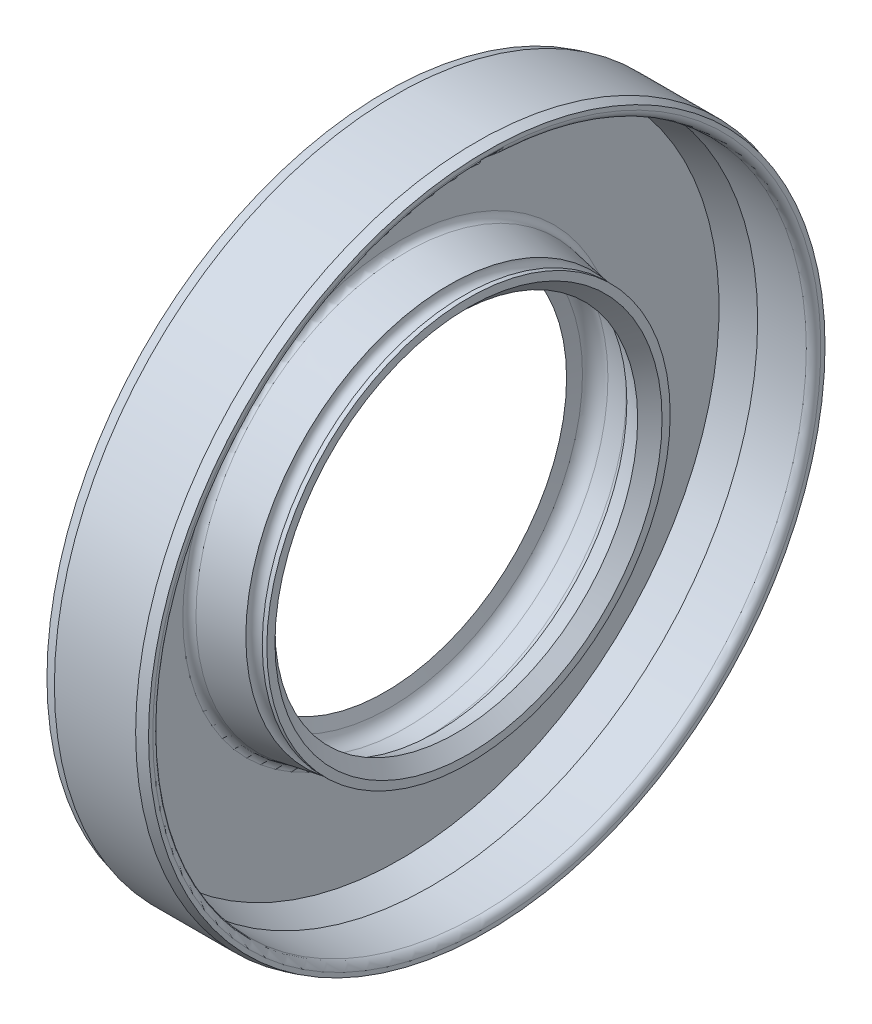
SolidWorks part; units mm, degrees
material "NBR"
ref_plane "Horní rovina" through (0, 0, 0) normal (0, 0, 1) x (1, 0, 0)
ref_plane "Přední rovina" through (0, 0, 0) normal (0, 1, 0) x (1, 0, 0)
ref_plane "Pravá rovina" through (0, 0, 0) normal (1, 0, 0) x (0, 0, -1)
sketch "Skica1" plane through (0, 0, 0) normal (0, 1, 0) x (1, 0, 0)
  line L14 (0, 0) -> (0, 15.5516) construction
  line L15 (0, 0) -> (14.0001, 0) construction
  line L16 (-2.4168, 12.5) -> (14.9149, 12.5) construction
  line L17 (4.9, -1.4676) -> (4.9, 13.2883) construction
  line L18 (7, 23.3124) -> (6.3, 23.5)
  line L19 (7, 23.3124) -> (7, 23.02)
  line L20 (6.5, 22.52) -> (3.15, 22.52)
  line L21 (3.15, 22.52) -> (1.05, 21.9573)
  line L22 (1.05, 21.9573) -> (1.05, 14.9984)
  line L23 (4.383, 13.9912) -> (1.4632, 14.506)
  line L24 (5.74, 13.9) -> (5.425, 13.9)
  line L25 (5.74, 13.9) -> (5.74, 13.34)
  line L26 (5.74, 13.34) -> (4.9, 12.5)
  line L27 (4.9, 12.5) -> (3.5, 13.1528)
  line L28 (2.9426, 13.672) -> (1.4069, 13.9428)
  line L29 (0, 14.6104) -> (0, 23.3124)
  line L30 (0.7, 23.5) -> (0, 23.3124)
  line L31 (6.3, 23.5) -> (0.7, 23.5)
  line L32 (0, 14.6104) -> (0, 12.5)
  line L33 (0, 12.5) -> (0.2944, 13.3024)
  arc A5 (6.5, 22.52) -> (7, 23.02) centre (6.5, 23.02) ccw
  arc A6 (1.05, 14.9984) -> (1.4632, 14.506) centre (1.55, 14.9984) ccw
  arc A8 (3.5, 13.1528) -> (2.9426, 13.672) centre (2.821, 12.9827) ccw
  arc A10 (0.2944, 13.3024) -> (1.4069, 13.9428) centre (1.2332, 12.958) cw
  arc A11 (4.383, 13.9912) -> (5.425, 13.9) centre (4.9, 13.9002) ccw
  dimension "D3" = 1
  dimension "D1" = 4.9
  dimension "D2" = 12.5
revolve "Rotovat1" add sketch "Skica1" angle 360 about L15
sketch "Skica2" plane through (0, 0, 0) normal (-1, 0, 0) x (0, 0, 1)
  circle A0 centre (0, 0) radius 20.5
  circle A1 centre (0, 0) radius 16.5
  circle A2 centre (0, 0) radius 23.5 construction
  circle A3 centre (0, 0) radius 23.5 construction
  dimension "D1" = 47
  dimension "D2" = 41
  dimension "D3" = 4
extrude "Odebrat vysunutím1" cut sketch "Skica2" against normal blind 0.1
sketch "Skica3" plane through (0.1, 0, 0) normal (-1, 0, 0) x (0, 0, 1)
  line L0 (0, 21.3866) -> (0, 0) construction
  line L1 (16.9559, 11.5216) -> (13.4802, 9.5149)
  line L3 (-1.5, 20.445) -> (-1.5, 16.4317)
  line L5 (1.5, 20.445) -> (1.5, 16.4317)
  line L6 (-1.2895, 20.4594) -> (1.213, 16.4553) construction
  line L7 (-1.213, 16.4553) -> (1.2895, 20.4594) construction
  line L8 (18.4559, 8.9235) -> (14.9802, 6.9168)
  line L9 (18.4559, -8.9235) -> (14.9802, -6.9168)
  line L10 (16.9559, -11.5216) -> (13.4802, -9.5149)
  line L11 (1.5, -20.445) -> (1.5, -16.4317)
  line L12 (-1.5, -20.445) -> (-1.5, -16.4317)
  line L13 (-16.9559, -11.5216) -> (-13.4802, -9.5149)
  line L14 (-18.4559, -8.9235) -> (-14.9802, -6.9168)
  line L15 (-18.4559, 8.9235) -> (-14.9802, 6.9168)
  line L16 (-16.9559, 11.5216) -> (-13.4802, 9.5149)
  circle A0 centre (0, 0) radius 16.5 construction
  circle A1 centre (0, 0) radius 20.5 construction
  arc A2 (-13.4802, 9.5149) -> (-14.9802, 6.9168) centre (0, 0) ccw
  arc A3 (-16.9559, 11.5216) -> (-18.4559, 8.9235) centre (0, 0) ccw
  arc A4 (1.5, 16.4317) -> (-1.5, 16.4317) centre (0, 0) ccw
  arc A5 (1.5, 20.445) -> (-1.5, 20.445) centre (0, 0) ccw
  arc A6 (14.9802, 6.9168) -> (13.4802, 9.5149) centre (0, 0) ccw
  arc A7 (18.4559, 8.9235) -> (16.9559, 11.5216) centre (0, 0) ccw
  arc A8 (-14.9802, -6.9168) -> (-13.4802, -9.5149) centre (0, 0) ccw
  arc A9 (-18.4559, -8.9235) -> (-16.9559, -11.5216) centre (0, 0) ccw
  arc A10 (-1.5, -16.4317) -> (1.5, -16.4317) centre (0, 0) ccw
  arc A11 (-1.5, -20.445) -> (1.5, -20.445) centre (0, 0) ccw
  arc A12 (13.4802, -9.5149) -> (14.9802, -6.9168) centre (0, 0) ccw
  arc A13 (16.9559, -11.5216) -> (18.4559, -8.9235) centre (0, 0) ccw
  point P3 (0, 18.3962)
  dimension "D1" = 6
extrude "Odebrat vysunutím2" cut sketch "Skica3" against normal blind 0.1
equation "\"D2@Skica2\"=\"D1@Skica2\"-6"
